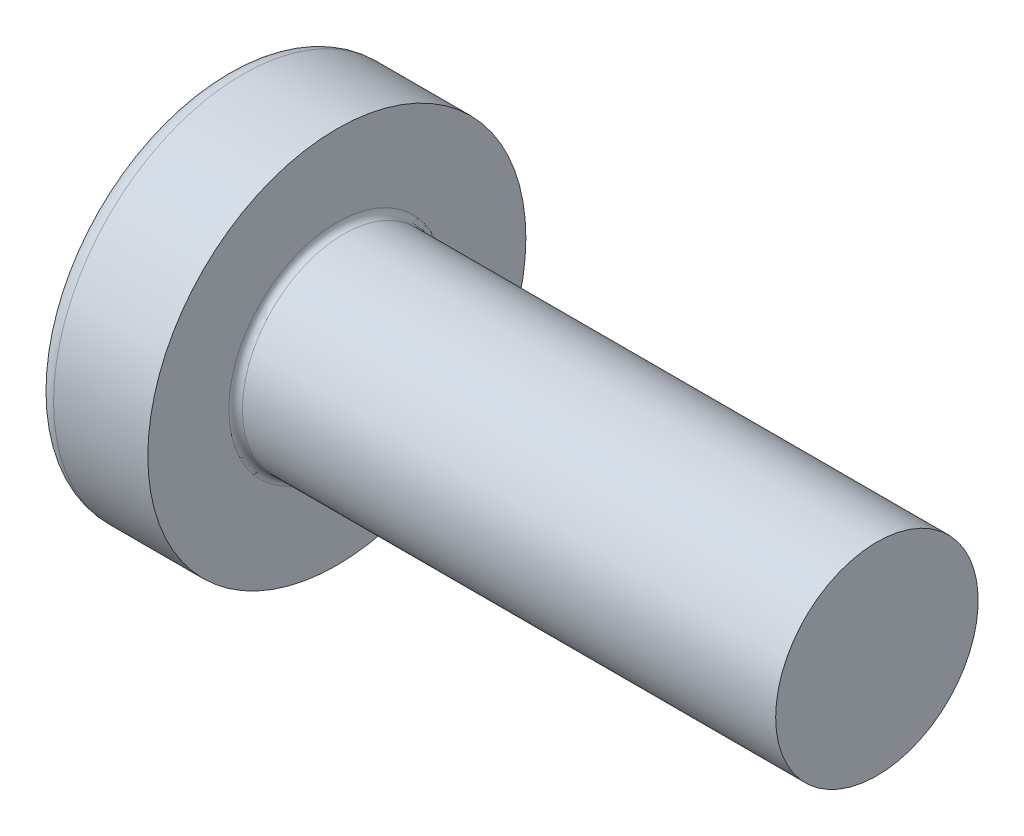
SolidWorks part; units mm, degrees
ref_plane "Plane1" through (0, 0, 0) normal (0, 0, 1) x (1, 0, 0)
ref_plane "Plane2" through (0, 0, 0) normal (0, 1, 0) x (1, 0, 0)
ref_plane "Plane3" through (0, 0, 0) normal (1, 0, 0) x (0, 0, -1)
sketch "BodySke" plane through (0, 0, 0) normal (0, 0, 1) x (1, 0, 0)
  line L0 (2.4, 1.5) -> (2.4, 2.8)
  line L1 (2.65, 6.35) -> (2.65, -3.175) construction
  line L2 (-25.4, 0) -> (127, 0) construction
  line L3 (10.4, 0) -> (0, 0)
  line L4 (2.4, 1.5) -> (10.4, 1.5)
  line L5 (10.4, 1.5) -> (10.4, 0)
  line L6 (1.0035, 2.8) -> (2.4, 2.8)
  line L8 (2.4, 6.35) -> (2.4, -3.175) construction
  arc A0 (0.7754, 2.6744) -> (0, 0) centre (5, 0) ccw
  arc A2 (0.7754, 2.6744) -> (1.0035, 2.8) centre (1.0035, 2.53) cw
  dimension "Head_crown_rad" = 5
  dimension "Head_fillet_rad" = 0.27
  dimension "Length" = 8
  dimension "Head_ht" = 2.4
  dimension "Head_dia" = 5.6
  dimension "Advance" = 0.5
  dimension "Thread_nom" = 8
  dimension "Diameter" = 3
revolve "Base-Revolve" add sketch "BodySke"
cosmetic thread "ThreadCosmetic" [suppressed]
fillet "Fillet1" radius 0.1 1 edges at (2.4, 0, 1.5)
sketch "Sketch3" plane through (0, 0, 0) normal (1, 0, 0) x (0, 0, -1)
  line L0 (0.37, -1.4) -> (-0.37, -1.4)
  line L1 (0.37, -1.4) -> (0.37, 1.4)
  line L2 (-0.37, 1.4) -> (0.37, 1.4)
  line L3 (-0.37, 1.4) -> (-0.37, -1.4)
  dimension "Cross_dia" = 2.8
  dimension "D1" = 1.4
  dimension "Cross_width" = 0.74
  dimension "D2" = 0.37
ref_plane "Plane4" through (1.75, 0, 0) normal (1, 0, 0) x (0, 0, -1)
sketch "Sketch4" plane through (1.75, 0, 0) normal (1, 0, 0) x (0, 0, -1)
  line L0 (0.37, -0.5275) -> (-0.37, -0.5275)
  line L1 (0.37, -0.5275) -> (0.37, 0.5275)
  line L2 (-0.37, 0.5275) -> (0.37, 0.5275)
  line L3 (-0.37, 0.5275) -> (-0.37, -0.5275)
  dimension "D1" = 0.74
  dimension "D2" = 1.055
  dimension "D3" = 0.37
  dimension "D4" = 0.5275
loft "Recess" cut profiles "Sketch3", "Sketch4"
pattern_circular "RecPat" count 2 every 90 about axis through (0, 0, 0) along (1, 0, 0) of "Recess"
sketch "RecCorSke" plane through (0, 0, 0) normal (0, 0, 1) x (1, 0, 0)
  line L0 (-3.175, 0) -> (15.875, 0) construction
  line L1 (-25.4, 0) -> (127, 0) construction
  line L2 (0, 0) -> (0, 0.6784)
  line L3 (0, 0.6784) -> (1.75, 0.556)
  line L4 (1.75, 0.556) -> (1.9307, 0)
  line L5 (1.9307, 0) -> (0, 0)
  dimension "Diameter" = 1.112
  dimension "Depth" = 1.75
  dimension "Draft_angle" = 4
  dimension "Bottom_angle" = 18
revolve "RecessCore" cut sketch "RecCorSke" angle 360 about L0
sketch "ThdSchSke" plane through (0, 0, 0) normal (0, 0, 1) x (1, 0, 0)
  line L0 (3.4, -1.2195) -> (3.2036, -1.5)
  line L1 (3.4, -1.2195) -> (3.5964, -1.5)
  line L2 (3.5964, -1.5) -> (3.5964, -1.875)
  line L3 (-3.175, 0) -> (5.1513, 0) construction
  line L5 (3.5964, -1.875) -> (3.2036, -1.875)
  line L6 (3.2036, -1.875) -> (3.2036, -1.5)
  dimension "Diameter" = 3
  dimension "SideAngle" = 55
  dimension "VeeAngle" = 70
  dimension "Thread_minor" = 2.439
  dimension "Overcut" = 3.75
  dimension "Start" = 3.4
revolve "ThreadSchematic" [suppressed] cut sketch "ThdSchSke" angle 360 about L3
pattern_linear "ThdSchPat" [suppressed]
equation "\"D1@Sketch3\" = \"Cross_dia@Sketch3\" / 2"
equation "\"D2@Sketch3\" = \"Cross_width@Sketch3\" / 2"
equation "\"Depth@RecCorSke\" = \"Cross_depth@Plane4\""
equation "\"D1@Sketch4\" = \"Cross_width@Sketch3\""
equation "\"D2@Sketch4\" = \"Cross_dia@Sketch3\" - 2.0 * \"Cross_depth@Plane4\" * tan(26.5  * 0.017453292)"
equation "\"D3@Sketch4\" = \"D1@Sketch4\" / 2"
equation "\"D4@Sketch4\" = \"D2@Sketch4\" / 2"
equation "\"Thread_length@ThreadCosmetic\" = ((sgn( (\"Length@BodySke\" - \"Advance@BodySke\" * 2.0 ) - \"Thread_nom@BodySke\" )-1)*( (\"Length@BodySke\" - \"Advance@BodySke\" * 2.0 ) - \"Thread_nom@BodySke\" ))/-2+ \"Thread_nom@BodySke\""
equation "\"Thread_minor@ThdSchSke\" = \"Thread_minor@ThreadCosmetic\""
equation "\"Diameter@ThdSchSke\" = \"Diameter@BodySke\""
equation "\"Overcut@ThdSchSke\" = \"Diameter@BodySke\" * 1.25"
equation "\"Start@ThdSchSke\" = \"Head_ht@BodySke\" + \"Length@BodySke\" - \"Thread_length@ThreadCosmetic\"  '---Non-countersunk---"
equation "\"Num_threads@ThdSchPat\" = int( \"Thread_length@ThreadCosmetic\" / \"Advance@BodySke\" + 0.999 )  + 1"
equation "\"Advance@ThdSchPat\" = \"Thread_length@ThreadCosmetic\" /  (\"Num_threads@ThdSchPat\" - 1) 'relax it"
